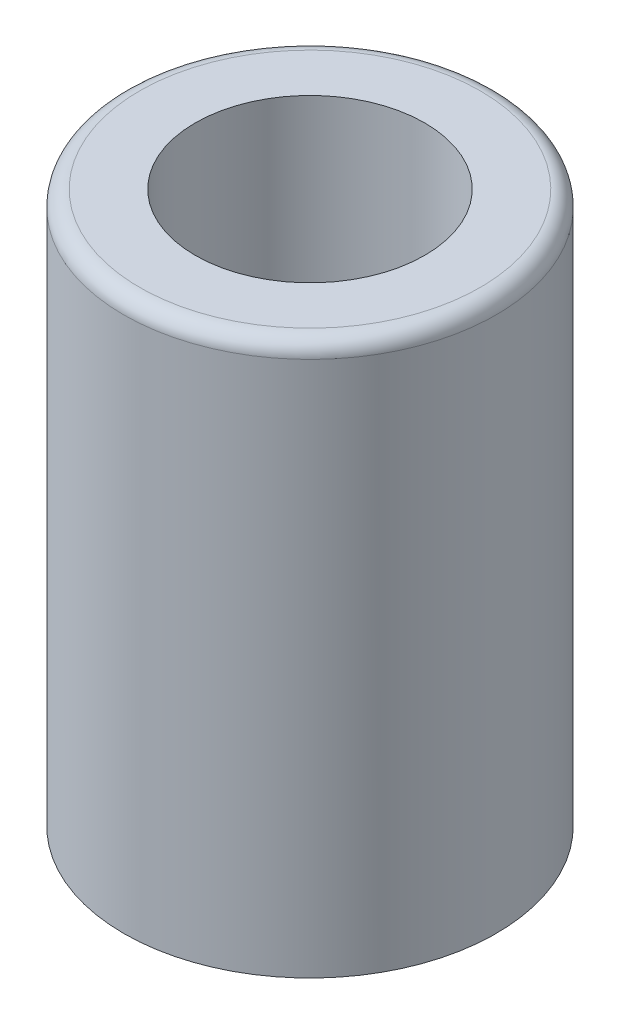
SolidWorks part; units mm, degrees
ref_plane "Front Plane" through (0, 0, 0) normal (0, 0, 1) x (1, 0, 0)
ref_plane "Top Plane" through (0, 0, 0) normal (0, 1, 0) x (1, 0, 0)
ref_plane "Right Plane" through (0, 0, 0) normal (1, 0, 0) x (0, 0, -1)
sketch "Sketch2" plane through (0, 0, 0) normal (0, 0, 1) x (1, 0, 0)
  line L0 (0, 0) -> (3.52, 0)
  line L1 (3.52, 0) -> (3.52, 10.43)
  line L2 (3.52, 10.43) -> (2.17, 10.43)
  line L3 (2.17, 10.43) -> (2.17, 3.8056)
  line L4 (2.17, 3.8056) -> (0, 3.8056)
  line L5 (0, 3.8056) -> (0, 0)
  dimension "D1" = 2.17
  dimension "D2" = 6.6244
revolve "Revolve1" add sketch "Sketch2" angle 360 about L5
fillet "Fillet1" radius 0.3 1 edges at (0, 10.43, 3.52)
